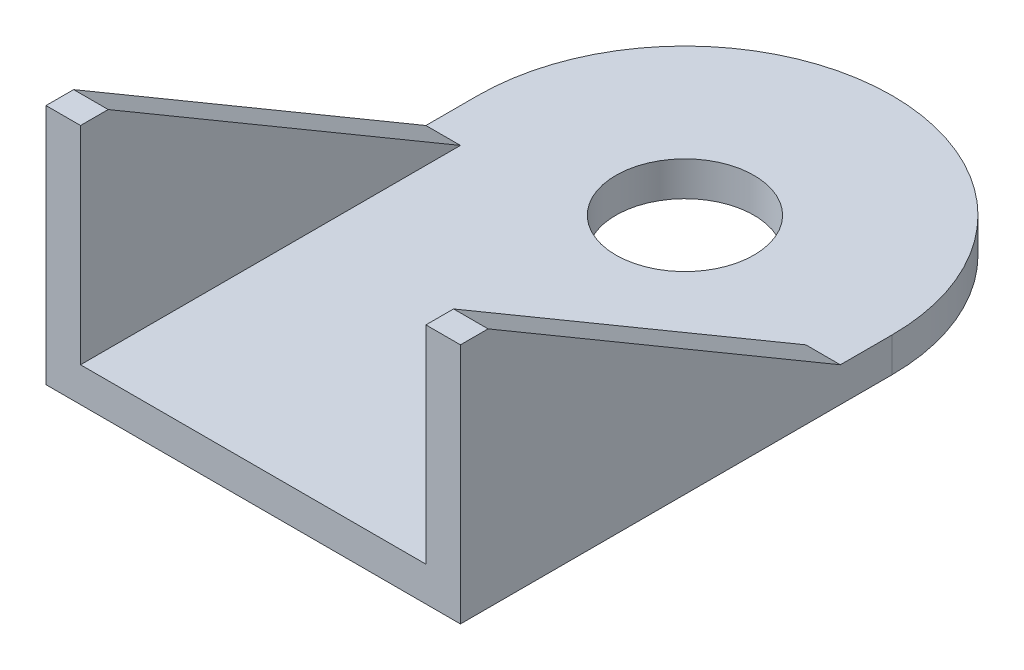
SolidWorks part; units mm, degrees
material "AISI 304"
ref_plane "前视基准面" through (0, 0, 0) normal (0, 0, 1) x (1, 0, 0)
ref_plane "上视基准面" through (0, 0, 0) normal (0, 1, 0) x (1, 0, 0)
ref_plane "右视基准面" through (0, 0, 0) normal (1, 0, 0) x (0, 0, -1)
sketch "草图1" plane through (0, 0, 0) normal (0, 1, 0) x (1, 0, 0)
  line L0 (-12, 0) -> (-12, -25)
  line L1 (-12, -25) -> (12, -25)
  line L2 (12, -25) -> (12, 0)
  circle A0 centre (0, 0) radius 4
  circle A1 centre (0, 0) radius 12
  dimension "D1" = 8
  dimension "D2" = 24
  dimension "D3" = 25
extrude "凸台-拉伸1" add sketch "草图1" along normal blind 2 contours A1 A0 | A1 L0 L1 L2
sketch "草图3" plane through (12, 0, 0) normal (1, 0, 0) x (0, 0, -1)
  line L0 (-25, 2) -> (-25, 14)
  line L1 (-25, 14) -> (-23.4, 14)
  line L2 (-23.4, 14) -> (-3, 2)
  line L4 (-25, 2) -> (0, 2) construction
  line L5 (-3, 2) -> (-25, 2)
  dimension "D1" = 1.6
  dimension "D4" = 12
extrude "凸台-拉伸2" add sketch "草图3" against normal blind 2
mirror "镜向1" about plane through (0, 0, 0) normal (1, 0, 0) of "凸台-拉伸2"
ref_plane "基准面1" through (0, 0, 0) normal (0, 0, 1) x (1, 0, 0)
sketch "草图4" [suppressed] plane through (0, 0, 0) normal (0, 0, 1) x (1, 0, 0)
  circle A0 centre (0, 0) radius 41.9162
sketch "草图7" plane through (0, 0, 0) normal (0, -1, 0) x (1, 0, 0)
  circle A0 centre (0, 0) radius 9
split line "分割线1"
sketch "草图8" plane through (0, 0, 0) normal (0, -1, 0) x (1, 0, 0)
  circle A0 centre (0, 0) radius 12
split line "分割线2"
